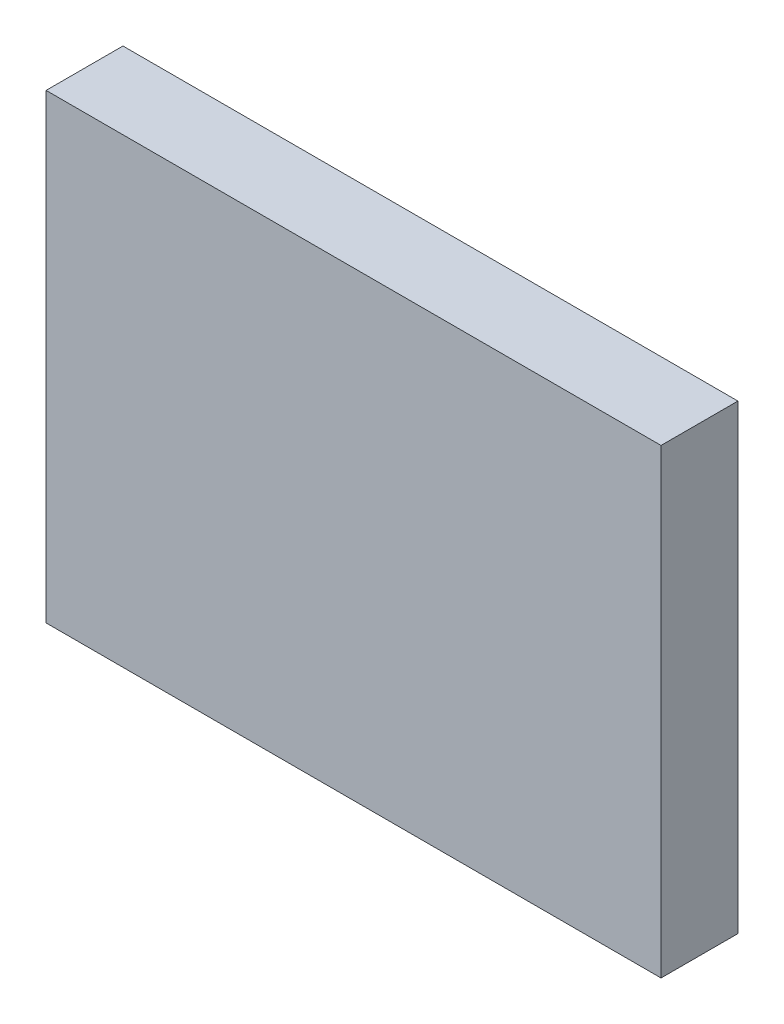
SolidWorks part; units mm, degrees
ref_plane "Front Plane" through (0, 0, 0) normal (0, 0, 1) x (1, 0, 0)
ref_plane "Top Plane" through (0, 0, 0) normal (0, 1, 0) x (1, 0, 0)
ref_plane "Right Plane" through (0, 0, 0) normal (1, 0, 0) x (0, 0, -1)
sketch "Sketch1" plane through (0, 0, 0) normal (0, 0, 1) x (1, 0, 0)
  line L1 (0, 0) -> (101.6, 0)
  line L2 (0, 0) -> (0, 76.2)
  line L3 (0, 76.2) -> (101.6, 76.2)
  line L4 (101.6, 0) -> (101.6, 76.2)
extrude "Boss-Extrude1" add sketch "Sketch1" along normal blind 12.7
sketch "Sketch2" plane through (0, 0, 0) normal (0, 0, 1) x (1, 0, 0)
  circle A0 centre (50.8, 38.1) radius 6.35
